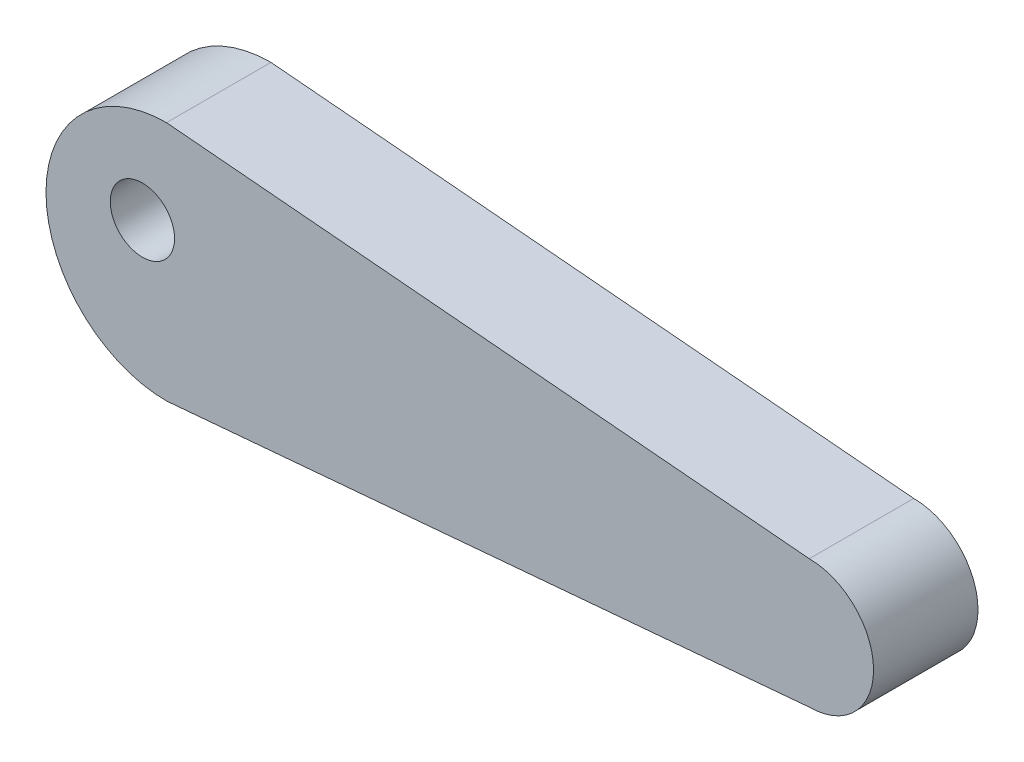
SolidWorks part; units mm, degrees
ref_plane "Front" through (0, 0, 0) normal (0, 0, 1) x (1, 0, 0)
ref_plane "Top" through (0, 0, 0) normal (0, 1, 0) x (1, 0, 0)
ref_plane "Right" through (0, 0, 0) normal (1, 0, 0) x (0, 0, -1)
sketch "Esquisse1" plane through (0, 0, 0) normal (0, 0, 1) x (1, 0, 0)
  line L0 (0, 0) -> (-17.4268, 0) construction
  line L1 (0, -15) -> (0, 15) construction
  line L2 (0, 15) -> (80, 8)
  line L3 (80, 8) -> (80, -8) construction
  line L4 (80, 0) -> (58.7134, 0) construction
  line L5 (0, -15) -> (80, -8)
  arc A0 (0, 15) -> (0, -15) centre (0, 0) ccw
  arc A1 (80, -8) -> (80, 8) centre (80, 0) ccw
  point P8 (0, 0)
  dimension "D2" = 15
  dimension "D3" = 8
  dimension "D1" = 80
extrude "Boss.-Extru.1" add sketch "Esquisse1" along normal blind 13
sketch "Esquisse2" plane through (0, 0, 13) normal (0, 0, 1) x (1, 0, 0)
  line L0 (0, 0) -> (0, 3) construction
  line L1 (0, 3) -> (-3, 3) construction
  circle A0 centre (-3, 3) radius 4
  point P5 (0, 0)
  dimension "D1" = 8
  dimension "D2" = 3
  dimension "D3" = 3
extrude "Enlèv. mat.-Extru.1" cut sketch "Esquisse2" against normal through all both and the other way through all
